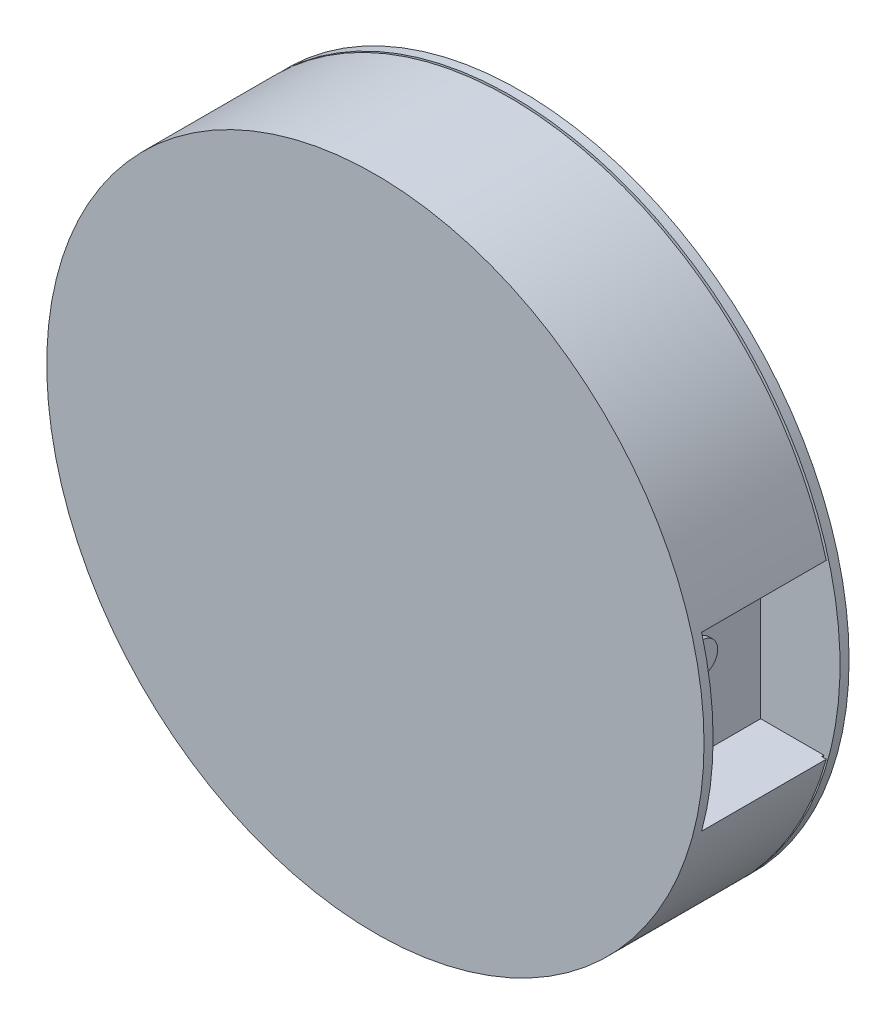
SolidWorks part; units mm, degrees
material "ABS"
ref_plane "Ebene vorne" through (0, 0, 0) normal (0, 0, 1) x (1, 0, 0)
ref_plane "Ebene oben" through (0, 0, 0) normal (0, 1, 0) x (1, 0, 0)
ref_plane "Ebene rechts" through (0, 0, 0) normal (1, 0, 0) x (0, 0, -1)
sketch "Skizze2" plane through (0, 0, 0) normal (0, 0, 1) x (1, 0, 0)
  circle A0 centre (0, 0) radius 72.5
  dimension "D1" = 145
extrude "Base " add sketch "Skizze2" along normal blind 32
sketch "Skizze3" plane through (0, 0, 0) normal (0, 1, 0) x (1, 0, 0)
  line L0 (72.5, -32) -> (72.5, 0) construction
  line L1 (72.5, -2.5) -> (71.5, -2.5)
  line L2 (72.5, -2.5) -> (72.5, -2)
  line L3 (72.5, -2) -> (71.5, -2)
  line L4 (71.5, -2.5) -> (71.5, -2)
  line L5 (72.5, 0) -> (-72.5, 0) construction
  line L6 (0, 0) -> (0, -32) construction
  line L7 (-72.5, -32) -> (72.5, -32) construction
  dimension "D1" = 0.5
  dimension "D2" = 2
  dimension "D3" = 1
revolve "Cover Seam" cut sketch "Skizze3" angle 360 about L6
ref_plane "Ebene1" through (72.5, 0, 0) normal (1, 0, 0) x (0, 0, -1)
sketch "Skizze4" plane through (72.5, 0, 0) normal (1, 0, 0) x (0, 0, -1)
  line L0 (0, 0) -> (-32, 0) construction
  line L1 (-32, 72.5) -> (-32, -72.5) construction
  line L3 (-30, -19) -> (-2, -19)
  line L4 (-30, -19) -> (-30, 19)
  line L5 (-30, 19) -> (-2, 19)
  line L6 (-2, -19) -> (-2, 19)
  line L7 (-30, -19) -> (-2, 19) construction
  line L8 (-30, 19) -> (-2, -19) construction
  point P4 (-16, 0)
  dimension "D1" = 2
  dimension "D2" = 38
extrude "Front Camera Cut" cut sketch "Skizze4" against normal blind 17.5
sketch "Skizze5" plane through (55, 0, 0) normal (1, 0, 0) x (0, 0, -1)
  line L0 (-30, -19) -> (-2, -19) construction
  line L1 (-30, 19) -> (-29, 19)
  line L2 (-30, 19) -> (-30, -19)
  line L3 (-30, -19) -> (-29, -19)
  line L4 (-29, 19) -> (-29, -19)
  dimension "D1" = 1
extrude "Front Detail" cut sketch "Skizze5" against normal blind 1
sketch "Skizze6" plane through (55, 0, 0) normal (1, 0, 0) x (0, 0, -1)
  line L0 (-32, 72.5) -> (-32, -72.5) construction
  line L1 (0, 0) -> (-32, 0) construction
  circle A0 centre (-16, 0) radius 3.5
  point P7 (0, 0)
  dimension "D1" = 7
extrude "Camera Detail" add sketch "Skizze6" along normal blind 1
